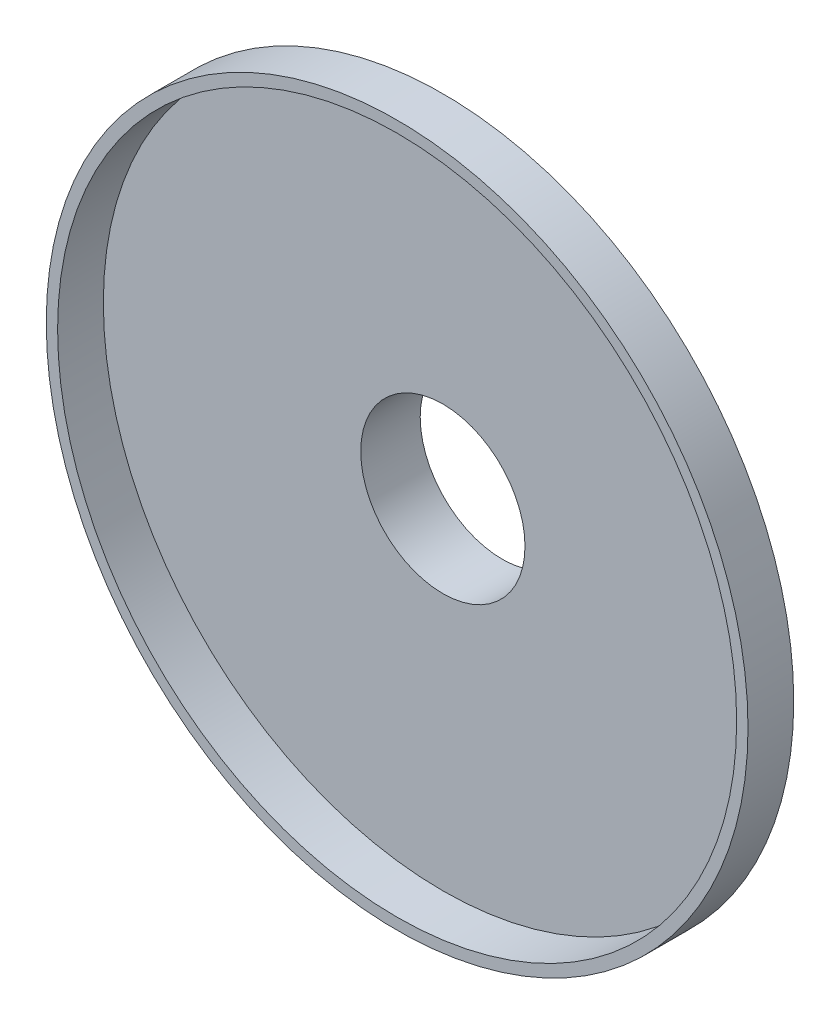
SolidWorks part; units mm, degrees
material "Rubber"
ref_plane "Front Plane" through (0, 0, 0) normal (0, 0, 1) x (1, 0, 0)
ref_plane "Top Plane" through (0, 0, 0) normal (0, 1, 0) x (1, 0, 0)
ref_plane "Right Plane" through (0, 0, 0) normal (1, 0, 0) x (0, 0, -1)
sketch "Sketch1" plane through (0, 0, 0) normal (0, 0, 1) x (1, 0, 0)
  circle A0 centre (0, 0) radius 76.73
extrude "Boss-Extrude1" add sketch "Sketch1" along normal blind 10 and the other way blind 8 draft 70
sketch "Sketch2" plane through (0, 0, -8) normal (0, 0, -1) x (-1, 0, 0)
  circle A0 centre (0, 0) radius 17.9565
extrude "Cut-Extrude1" cut sketch "Sketch2" against normal up to surface (18 mm away) up to face at (76.73, 0, 10)
sketch "Sketch3" plane through (0, 0, 10) normal (0, 0, 1) x (1, 0, 0)
  circle A0 centre (0, 0) radius 74.2478
extrude "Cut-Extrude2" cut sketch "Sketch3" against normal blind 10
sketch "Sketch4" plane through (0, 0, -8) normal (0, 0, -1) x (-1, 0, 0)
  circle A0 centre (0, 0) radius 19.1696
  circle A1 centre (0, 0) radius 17.9565
extrude "Boss-Extrude2" add sketch "Sketch4" along normal blind 5
